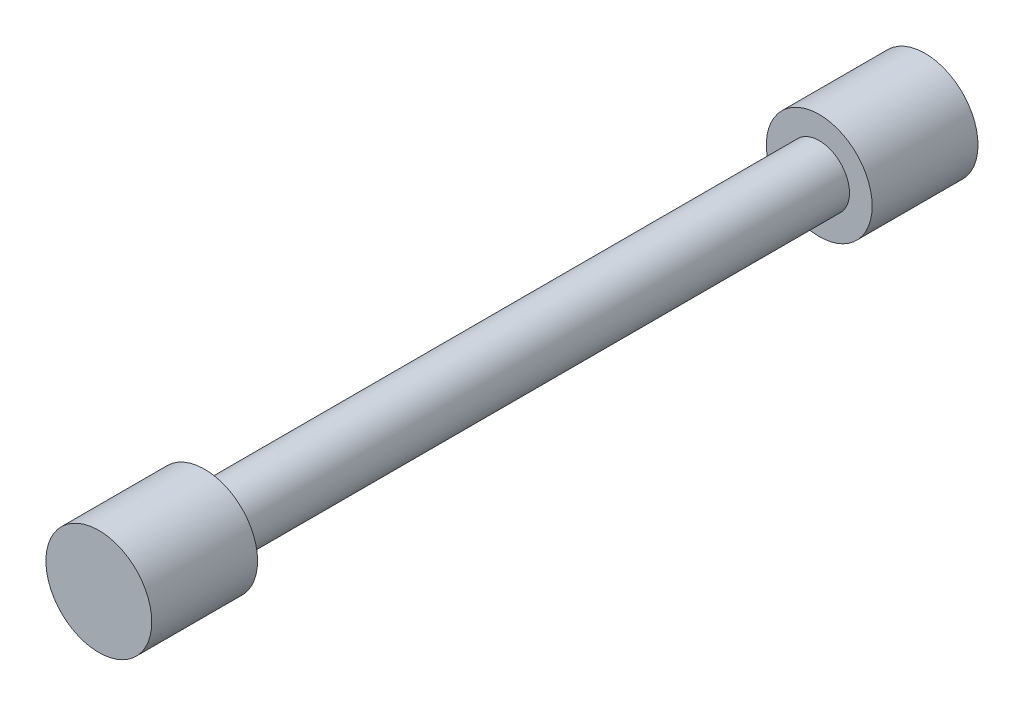
SolidWorks part; units mm, degrees
material "AISI 1045 Steel, cold drawn"
ref_plane "Front Plane" through (0, 0, 0) normal (0, 0, 1) x (1, 0, 0)
ref_plane "Top Plane" through (0, 0, 0) normal (0, 1, 0) x (1, 0, 0)
ref_plane "Right Plane" through (0, 0, 0) normal (1, 0, 0) x (0, 0, -1)
sketch "SK_Rod" plane through (0, 0, 0) normal (0, 1, 0) x (1, 0, 0)
  line L0 (0, -10) -> (0, 105.289) construction
  line L1 (0, -7) -> (7, -7)
  line L2 (7, -7) -> (7, 7)
  line L3 (7, 7) -> (4, 7)
  line L4 (4, 7) -> (4, 88.289)
  line L5 (4, 88.289) -> (7, 88.289)
  line L6 (7, 88.289) -> (7, 102.289)
  line L7 (7, 102.289) -> (0, 102.289)
  line L8 (0, 102.289) -> (0, -7)
  dimension "P1" = 10
  dimension "P2" = 105.289
  dimension "P3" = 7
  dimension "P4" = 7
  dimension "P5" = 7
  dimension "P6" = 7
  dimension "P7" = 7
  dimension "P8" = 4
  dimension "P9" = 7
  dimension "P10" = 4
  dimension "P11" = 88.289
  dimension "P12" = 7
  dimension "P13" = 88.289
  dimension "P14" = 7
  dimension "P15" = 102.289
  dimension "P16" = 102.289
revolve "Rod_Body" add sketch "SK_Rod" angle 360 about L0
sketch "SK_Ends" plane through (0, 0, 0) normal (0, 1, 0) x (1, 0, 0)
  point P0 (0, 0)
  point P2 (0, 95.289)
  dimension "P1" = 95.289
equation "\"Rod_length\"= 95.289"
